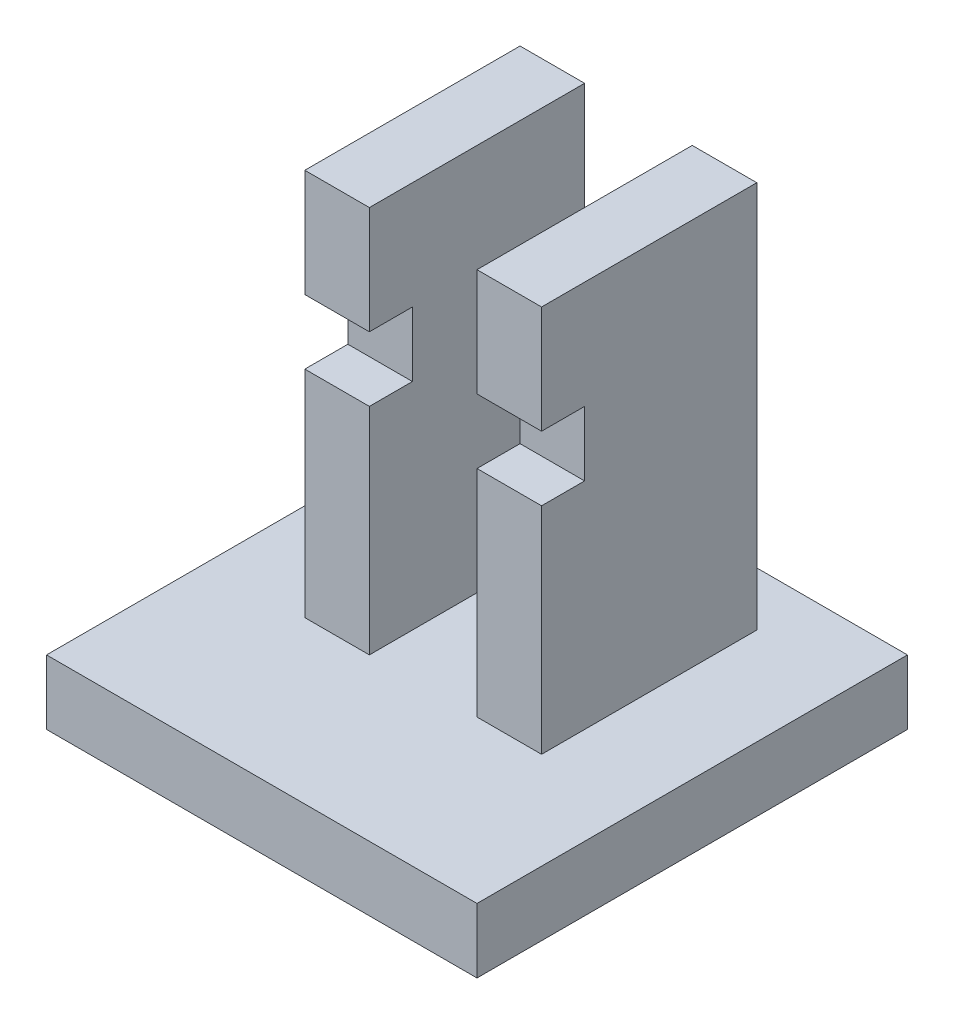
SolidWorks part; units mm, degrees
ref_plane "Front Plane" through (0, 0, 0) normal (0, 0, 1) x (1, 0, 0)
ref_plane "Top Plane" through (0, 0, 0) normal (0, 1, 0) x (1, 0, 0)
ref_plane "Right Plane" through (0, 0, 0) normal (1, 0, 0) x (0, 0, -1)
sketch "Sketch1" plane through (0, 0, 0) normal (0, 1, 0) x (1, 0, 0)
  line L0 (-26.3753, 0) -> (26.3753, 0) construction
  line L2 (-5.5, -5) -> (-2.5, -5)
  line L3 (-5.5, -5) -> (-5.5, 5)
  line L4 (-5.5, 5) -> (-2.5, 5)
  line L5 (-2.5, -5) -> (-2.5, 5)
  line L6 (-5.5, -5) -> (-2.5, 5) construction
  line L7 (-5.5, 5) -> (-2.5, -5) construction
  line L8 (2.5, -5) -> (5.5, -5)
  line L9 (2.5, -5) -> (2.5, 5)
  line L10 (2.5, 5) -> (5.5, 5)
  line L11 (5.5, -5) -> (5.5, 5)
  line L12 (2.5, -5) -> (5.5, 5) construction
  line L13 (2.5, 5) -> (5.5, -5) construction
  point P0 (-4, 0)
  point P4 (0, 0)
  point P9 (4, 0)
  dimension "D1" = 3
  dimension "D2" = 10
  dimension "D3" = 3
  dimension "D4" = 10
  dimension "D5" = 4
  dimension "D6" = 4
  dimension "D7" = 5
extrude "Boss-Extrude1" add sketch "Sketch1" along normal blind 18
sketch "Sketch2" plane through (0, 0, 0) normal (0, -1, 0) x (1, 0, 0)
  line L1 (-10, 7.5) -> (10, 7.5)
  line L2 (-10, 7.5) -> (-10, -7.5)
  line L3 (-10, -7.5) -> (10, -7.5)
  line L4 (10, 7.5) -> (10, -7.5)
  line L5 (-10, 7.5) -> (10, -7.5) construction
  line L6 (-10, -7.5) -> (10, 7.5) construction
  line L7 (10, 7.5) -> (-10, 7.5)
  line L8 (10, 7.5) -> (10, 12.5)
  line L9 (10, 12.5) -> (-10, 12.5)
  line L10 (-10, 7.5) -> (-10, 12.5)
  point P0 (0, 0)
  line M5 (5.5, -5) -> (5.5, 5)
  line M6 (5.5, 5) -> (2.5, 5)
  line M7 (2.5, 5) -> (2.5, -5)
  line M8 (2.5, -5) -> (5.5, -5)
  dimension "D1" = 15
  dimension "D2" = 20
  dimension "D3" = 20
  dimension "D4" = 5
extrude "Boss-Extrude2" add sketch "Sketch2" along normal blind 3 contours L10 L1 L8 L9 M6 | L4 L1 L3 M5 | M8 M5 M6 M7 | L2 L3 L1 M7
sketch "Sketch3" plane through (0, 0, 5) normal (0, 0, 1) x (1, 0, 0)
  line L0 (-5.5, 18) -> (-5.5, 0) construction
  line L1 (-5.5, 13) -> (5.5, 13)
  line L2 (-5.5, 13) -> (-5.5, 10)
  line L3 (-5.5, 10) -> (5.5, 10)
  line L4 (5.5, 13) -> (5.5, 10)
  line L5 (5.5, 18) -> (5.5, 0) construction
  line L6 (-5.5, 18) -> (-2.5, 18) construction
  dimension "D1" = 5
  dimension "D2" = 3
extrude "Cut-Extrude1" cut sketch "Sketch3" against normal blind 2
